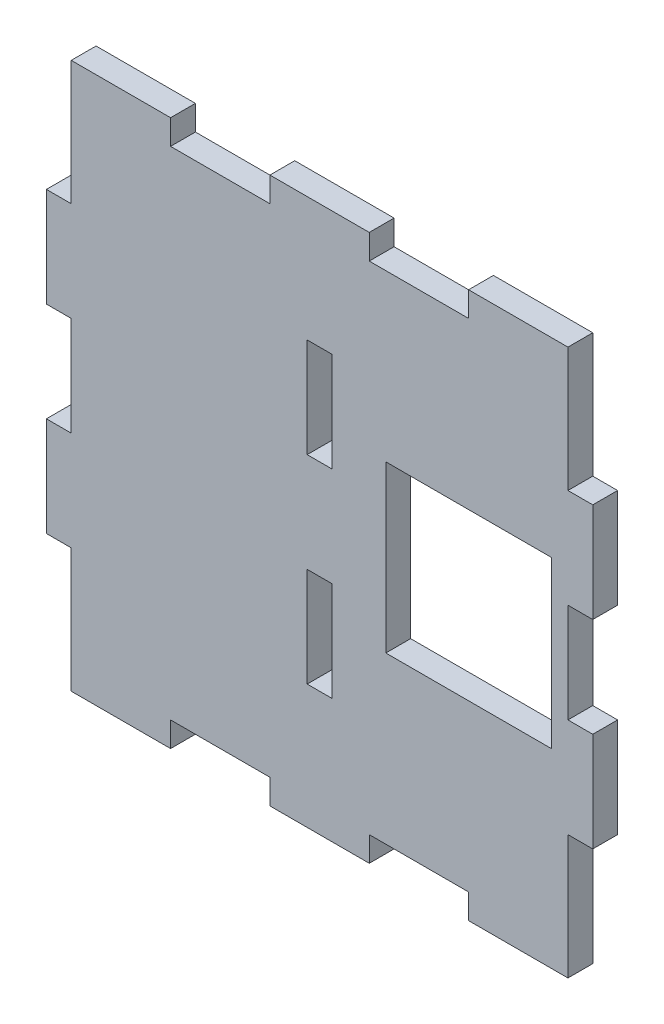
SolidWorks part; units mm, degrees
material "Pinho"
ref_plane "Plano frontal" through (0, 0, 0) normal (0, 0, 1) x (1, 0, 0)
ref_plane "Plano superior" through (0, 0, 0) normal (0, 1, 0) x (1, 0, 0)
ref_plane "Plano direito" through (0, 0, 0) normal (1, 0, 0) x (0, 0, -1)
sketch "Esboço1" plane through (0, 0, 0) normal (0, 0, 1) x (1, 0, 0)
  line L0 (-31.2169, 10.5171) -> (-31.2169, -1.4829)
  line L1 (-19.2169, 34.5171) -> (-7.2169, 34.5171)
  line L2 (-31.2169, 34.5171) -> (-31.2169, 22.5171)
  line L3 (-19.2169, -25.4829) -> (-7.2169, -25.4829)
  line L4 (28.7831, 34.5171) -> (28.7831, 22.5171)
  line L5 (-31.2169, -13.4829) -> (-31.2169, -25.4829)
  line L6 (-31.2169, 10.5171) -> (-34.2169, 10.5171)
  line L7 (4.7831, 34.5171) -> (16.7831, 34.5171)
  line L9 (-31.2169, 22.5171) -> (-34.2169, 22.5171)
  line L10 (-34.2169, 10.5171) -> (-34.2169, 22.5171)
  line L12 (-31.2169, 34.5171) -> (-31.2169, 37.5171)
  line L13 (-34.2169, -13.4829) -> (-31.2169, -13.4829)
  line L14 (-34.2169, -13.4829) -> (-34.2169, -1.4829)
  line L15 (-34.2169, -1.4829) -> (-31.2169, -1.4829)
  line L17 (-31.2169, 37.5171) -> (-19.2169, 37.5171)
  line L18 (-19.2169, 34.5171) -> (-19.2169, 37.5171)
  line L20 (28.7831, 34.5171) -> (28.7831, 37.5171)
  line L21 (28.7831, 37.5171) -> (16.7831, 37.5171)
  line L22 (16.7831, 34.5171) -> (16.7831, 37.5171)
  line L24 (-7.2169, 34.5171) -> (-7.2169, 37.5171)
  line L25 (-7.2169, 37.5171) -> (4.7831, 37.5171)
  line L26 (4.7831, 34.5171) -> (4.7831, 37.5171)
  line L27 (28.7831, -13.4829) -> (28.7831, -25.4829)
  line L28 (28.7831, 10.5171) -> (31.7831, 10.5171)
  line L30 (28.7831, 22.5171) -> (31.7831, 22.5171)
  line L31 (31.7831, 10.5171) -> (31.7831, 22.5171)
  line L32 (4.7831, -25.4829) -> (16.7831, -25.4829)
  line L34 (28.7831, -13.4829) -> (31.7831, -13.4829)
  line L36 (28.7831, -1.4829) -> (31.7831, -1.4829)
  line L37 (31.7831, -13.4829) -> (31.7831, -1.4829)
  line L38 (28.7831, 10.5171) -> (28.7831, -1.4829)
  line L39 (-31.2169, -25.4829) -> (-31.2169, -28.4829)
  line L40 (-31.2169, -28.4829) -> (-19.2169, -28.4829)
  line L41 (-19.2169, -25.4829) -> (-19.2169, -28.4829)
  line L43 (28.7831, -25.4829) -> (28.7831, -28.4829)
  line L44 (28.7831, -28.4829) -> (16.7831, -28.4829)
  line L45 (16.7831, -25.4829) -> (16.7831, -28.4829)
  line L47 (-7.2169, -25.4829) -> (-7.2169, -28.4829)
  line L48 (-7.2169, -28.4829) -> (4.7831, -28.4829)
  line L49 (4.7831, -25.4829) -> (4.7831, -28.4829)
  line L50 (-1.2169, 37.5171) -> (-1.2169, -28.4829) construction
  line L51 (-31.2169, 4.5171) -> (28.7831, 4.5171) construction
  line L52 (-2.7169, 22.5171) -> (0.2831, 22.5171)
  line L53 (-2.7169, 22.5171) -> (-2.7169, 10.5171)
  line L54 (-2.7169, 10.5171) -> (0.2831, 10.5171)
  line L55 (0.2831, 22.5171) -> (0.2831, 10.5171)
  line L56 (-2.7169, 22.5171) -> (0.2831, 10.5171) construction
  line L57 (-2.7169, 10.5171) -> (0.2831, 22.5171) construction
  line L58 (-2.7169, -1.4829) -> (0.2831, -1.4829)
  line L59 (-2.7169, -1.4829) -> (-2.7169, -13.4829)
  line L60 (-2.7169, -13.4829) -> (0.2831, -13.4829)
  line L61 (0.2831, -1.4829) -> (0.2831, -13.4829)
  line L62 (-2.7169, -1.4829) -> (0.2831, -13.4829) construction
  line L63 (-2.7169, -13.4829) -> (0.2831, -1.4829) construction
  line L65 (6.7831, -5.4829) -> (26.7831, -5.4829)
  line L66 (6.7831, -5.4829) -> (6.7831, 14.5171)
  line L67 (6.7831, 14.5171) -> (26.7831, 14.5171)
  line L68 (26.7831, -5.4829) -> (26.7831, 14.5171)
  line L69 (6.7831, -5.4829) -> (26.7831, 14.5171) construction
  line L70 (6.7831, 14.5171) -> (26.7831, -5.4829) construction
  point P0 (0, 0)
  point P22 (-1.2169, 16.5171)
  point P49 (-1.2169, -7.4829)
  point P56 (16.7831, 4.5171)
  point P62 (28.7831, 4.5171)
  dimension "D1" = 60
  dimension "D2" = 60
  dimension "D3" = 12
  dimension "D4" = 12
  dimension "D5" = 12
  dimension "D6" = 12
  dimension "D7" = 12
  dimension "D8" = 12
  dimension "D9" = 12
  dimension "D10" = 12
  dimension "D11" = 12
  dimension "D12" = 12
  dimension "D13" = 12
  dimension "D14" = 12
  dimension "D15" = 12
  dimension "D16" = 12
  dimension "D17" = 3
  dimension "D18" = 3
  dimension "D19" = 3
  dimension "D20" = 3
  dimension "D21" = 3
  dimension "D22" = 3
  dimension "D23" = 3
  dimension "D24" = 3
  dimension "D25" = 3
  dimension "D26" = 3
  dimension "D27" = 3
  dimension "D28" = 3
  dimension "D29" = 3
  dimension "D30" = 12
  dimension "D31" = 3
  dimension "D32" = 12
  dimension "D33" = 12
  dimension "D34" = 12
  dimension "D35" = 12
  dimension "D36" = 3
  dimension "D37" = 3
  dimension "D38" = 20
  dimension "D39" = 20
  dimension "D40" = 2
extrude "Ressalto-extrusão1" add sketch "Esboço1" along normal blind 3
